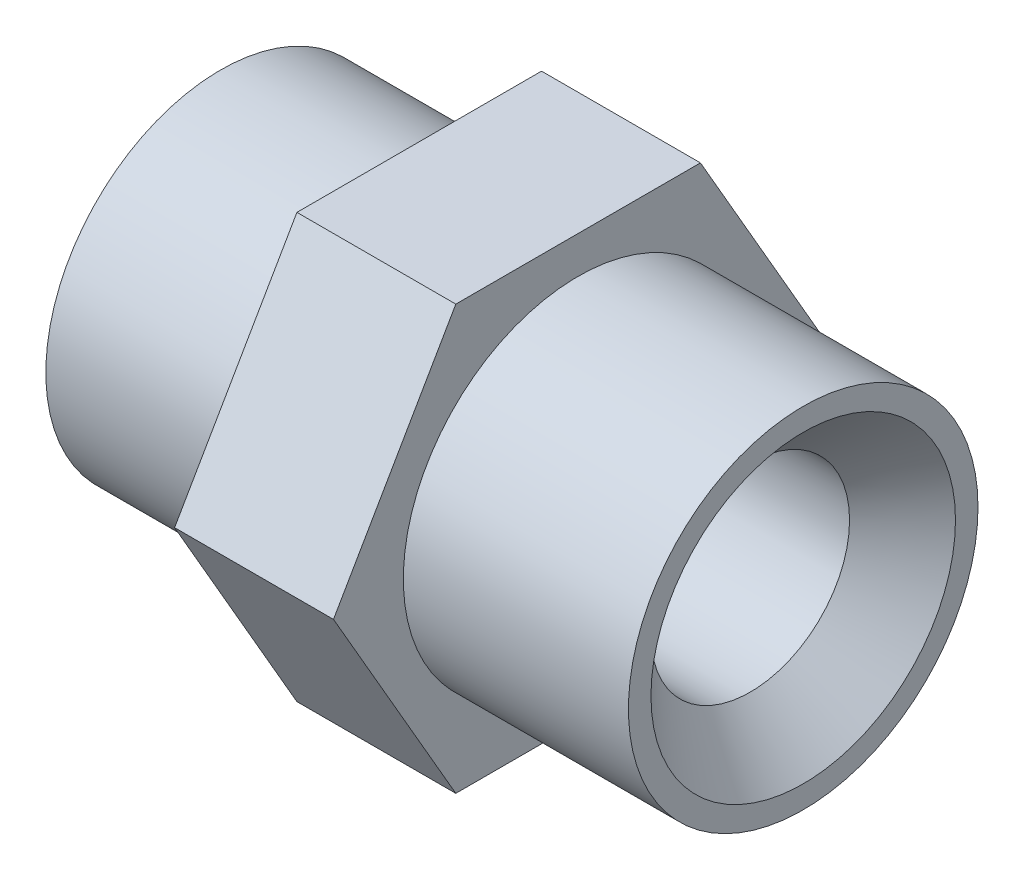
SolidWorks part; units mm, degrees
ref_plane "Front Plane" through (0, 0, 0) normal (0, 0, 1) x (1, 0, 0)
ref_plane "Top Plane" through (0, 0, 0) normal (0, 1, 0) x (1, 0, 0)
ref_plane "Right Plane" through (0, 0, 0) normal (1, 0, 0) x (0, 0, -1)
sketch "Szkic1" plane through (0, 0, 0) normal (1, 0, 0) x (0, 0, -1)
  circle A0 centre (0, 0) radius 7.5
  circle A1 centre (0, 0) radius 13.2
  dimension "D1" = 15
  dimension "D2" = 26.4
extrude "Dodanie-wyciągnięcie1" add sketch "Szkic1" along normal blind 44
sketch3d "Szkic 3D1"
  line L0 (15, 0, 0) -> (15, 9.9704, -12.5136)
  circle A0 centre (15, 0, 0) radius 16
  point P2 (31, 0, 0)
  dimension "D2" = 32
  dimension "D1" = 29
sketch "Szkic6" plane through (15, 0, 0) normal (1, 0, 0) x (0, 0, -1)
  line L1 (18.4752, 0) -> (9.2376, 16)
  line L2 (9.2376, 16) -> (-9.2376, 16)
  line L3 (-9.2376, 16) -> (-18.4752, 0)
  line L4 (-18.4752, 0) -> (-9.2376, -16)
  line L5 (-9.2376, -16) -> (9.2376, -16)
  line L6 (9.2376, -16) -> (18.4752, 0)
  circle A0 centre (0, 0) radius 16 construction
extrude "Dodanie-wyciągnięcie2" add sketch "Szkic6" along normal blind 12
chamfer "Sfazowanie1" distance 4 angle 45 1 edges at (44, 0, -7.5)
sketch "Szkic8" plane through (15, 0, 0) normal (-1, 0, 0) x (0, 0, 1)
  circle A0 centre (0, 0) radius 7.5
extrude "Wytnij-wyciągnięcie1" cut sketch "Szkic8" against normal blind 12
chamfer "Sfazowanie2" distance 4 angle 45 1 edges at (0, 0, -7.5)
